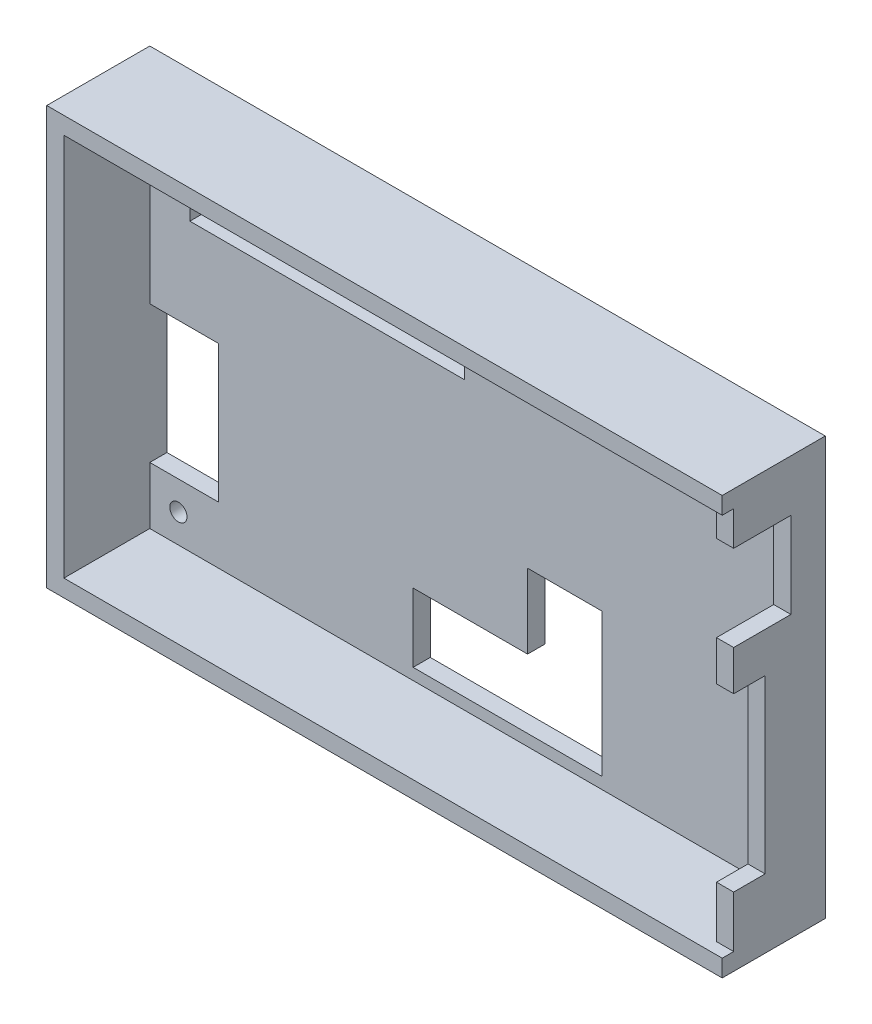
SolidWorks part; units mm, degrees
ref_plane "前视基准面" through (0, 0, 0) normal (0, 0, 1) x (1, 0, 0)
ref_plane "上视基准面" through (0, 0, 0) normal (0, 1, 0) x (1, 0, 0)
ref_plane "右视基准面" through (0, 0, 0) normal (1, 0, 0) x (0, 0, -1)
other "Configuration Table"
sketch "草图1" plane through (0, 0, 0) normal (0, 0, 1) x (1, 0, 0)
  line L4 (-32.176, 32.685) -> (85.824, 32.685)
  line L15 (85.824, 32.685) -> (85.824, -40.315)
  line L16 (85.824, -40.315) -> (-32.176, -40.315)
  line L17 (-32.176, -40.315) -> (-32.176, 32.685)
  circle A0 centre (-24.176, 24.685) radius 1.5
  circle A1 centre (-24.176, -32.315) radius 1.5
  circle A2 centre (77.824, 24.685) radius 1.5
  circle A3 centre (77.824, -32.315) radius 1.5
extrude "凸台-拉伸1" add sketch "草图1" along normal blind 3
sketch "草图2" plane through (0, 0, 3) normal (0, 0, 1) x (1, 0, 0)
  line L0 (-32.176, 32.685) -> (-32.176, 29.685)
  line L1 (-32.176, 32.685) -> (-32.176, -40.315) construction
  line L3 (85.824, -40.315) -> (85.824, 32.685) construction
  line L4 (85.824, 29.685) -> (85.824, 32.685)
  line L5 (85.824, 32.685) -> (-32.176, 32.685)
  line L6 (-32.176, -40.315) -> (-32.176, -37.315)
  line L7 (-32.176, -40.315) -> (85.824, -40.315) construction
  line L9 (85.824, -37.315) -> (85.824, -40.315)
  line L10 (85.824, -40.315) -> (-32.176, -40.315)
  line L11 (85.824, -37.315) -> (-29.176, -37.315)
  line L12 (-29.176, -37.315) -> (-29.176, 29.685)
  line L13 (-29.176, 29.685) -> (85.824, 29.685)
  line L14 (-32.176, -37.315) -> (-32.176, 29.685)
extrude "凸台-拉伸2" add sketch "草图2" along normal blind 15
sketch "草图3" plane through (0, 0, 3) normal (0, 0, 1) x (1, 0, 0)
  line L0 (85.824, 29.685) -> (85.824, 23.685)
  line L1 (85.824, -37.315) -> (85.824, 29.685) construction
  line L3 (82.824, 23.685) -> (82.824, 29.685)
  line L4 (82.824, 29.685) -> (85.824, 29.685)
  line L5 (82.824, 23.685) -> (85.824, 23.685)
  line L6 (85.824, 23.685) -> (85.824, 8.685) construction
  line L7 (85.824, 8.685) -> (85.824, 3.6182)
  line L8 (82.824, 8.685) -> (82.824, 1.685)
  line L9 (82.824, 1.685) -> (85.824, 1.685)
  line L10 (85.824, 1.685) -> (85.824, 8.685)
  line L11 (85.824, 8.685) -> (82.824, 8.685)
  line L12 (85.824, 1.685) -> (85.824, -28.315)
  line L13 (85.824, -28.315) -> (85.824, -37.315)
  line L14 (85.824, -37.315) -> (82.824, -37.315)
  line L15 (85.824, -37.315) -> (-29.176, -37.315) construction
  line L16 (82.824, -37.315) -> (82.824, -28.315)
  line L17 (82.824, -28.315) -> (85.2282, -28.315)
  line L18 (85.2282, -28.315) -> (85.824, -28.315)
  line M9 (85.824, 29.685) -> (-29.176, 29.685)
  line M11 (-29.176, -37.315) -> (85.824, -37.315)
  line M12 (85.824, -37.315) -> (85.824, 29.685)
extrude "凸台-拉伸3" add sketch "草图3" along normal blind 13 contours L11 L8 L9 M12 | L3 L5 M12 M9 | L18 L17 L16 M11 M12
sketch "草图4" plane through (0, 0, 3) normal (0, 0, 1) x (1, 0, 0)
  line L0 (85.824, 23.685) -> (85.824, 8.685)
  line L1 (85.824, 8.685) -> (82.824, 8.685)
  line L2 (82.824, 8.685) -> (82.824, 23.685)
  line L3 (82.824, 23.685) -> (85.824, 23.685)
extrude "凸台-拉伸4" add sketch "草图4" along normal blind 3
sketch "草图5" plane through (0, 0, 3) normal (0, 0, 1) x (1, 0, 0)
  line L0 (85.824, 1.685) -> (82.824, 1.685)
  line L1 (82.824, 1.685) -> (82.824, -28.315)
  line L2 (82.824, -28.315) -> (85.824, -28.315)
  line L3 (85.824, -28.315) -> (85.824, 1.685)
extrude "凸台-拉伸5" add sketch "草图5" along normal blind 7.5
sketch "草图6" plane through (0, 0, 3) normal (0, 0, 1) x (1, 0, 0)
  line L0 (-22.176, 23.185) -> (-22.176, 12.685)
  line L3 (-22.176, 12.685) -> (25.824, 12.685)
  line L6 (-22.176, 23.185) -> (25.824, 23.185)
  line L7 (25.824, 23.185) -> (25.824, 12.685)
sketch "草图7" plane through (0, 0, 3) normal (0, 0, 1) x (1, 0, 0)
  line L0 (16.824, -35.315) -> (16.824, -23.315)
  line L1 (-29.176, -37.315) -> (-29.176, 29.685) construction
  line L2 (-29.176, -3.315) -> (-17.176, -3.315)
  line L3 (-17.176, -3.315) -> (-17.176, -27.315)
  line L4 (-17.176, -27.315) -> (-29.176, -27.315)
  line L5 (-29.176, -37.315) -> (-29.176, 29.685) construction
  line L6 (-29.176, -27.315) -> (-29.176, -3.315)
  line L9 (16.824, -23.315) -> (36.824, -23.315)
  line L10 (36.824, -23.315) -> (36.824, -10.315)
  line L11 (36.824, -10.315) -> (49.824, -10.315)
  line L12 (49.824, -10.315) -> (49.824, -35.315)
  line L13 (49.824, -35.315) -> (16.824, -35.315)
extrude "切除-拉伸2" cut sketch "草图7" against normal blind 3
extrude "切除-拉伸4" cut sketch "草图6" against normal blind 3
